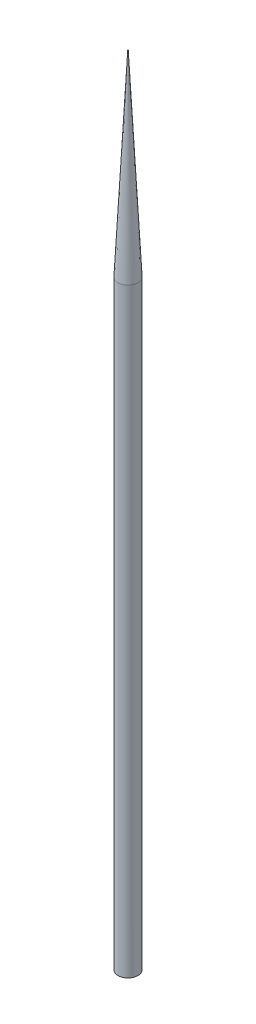
SolidWorks part; units mm, degrees
ref_plane "Спереди" through (0, 0, 0) normal (0, 0, 1) x (1, 0, 0)
ref_plane "Сверху" through (0, 0, 0) normal (0, 1, 0) x (1, 0, 0)
ref_plane "Справа" through (0, 0, 0) normal (1, 0, 0) x (0, 0, -1)
other "Configuration Table"
sketch "Эскиз1" plane through (0, 0, 0) normal (0, 1, 0) x (1, 0, 0)
  circle A0 centre (0, 0) radius 0.5
  point P4 (0, 0)
  dimension "D1" = 1
sketch "Эскиз2" plane through (0, 0, 0) normal (0, 0, 1) x (1, 0, 0)
  line L0 (0, -20.7889) -> (0, 9.2111)
  dimension "D1" = 30
  dimension "D3" = 20.7889
sweep "По траектории1" add profiles "Эскиз1" path "Эскиз2"
sketch "Эскиз5" plane through (0, 0, 0) normal (1, 0, 0) x (0, 0, -1)
  line L0 (0, 9.2111) -> (0, 19.2111) construction
  line L2 (0, 19.2111) -> (0.5, 9.2111)
  line L3 (0.5, 9.2111) -> (0, 9.2111) construction
  line L4 (0.5, 9.2111) -> (0, 9.2111)
  line L5 (0, 9.2111) -> (0, 19.2111)
  dimension "D1" = 10
revolve "Повернуть1" add sketch "Эскиз5" angle 360 about L5
scale "Масштаб1" bodies to scale 105 scale about centroid uniform scaling yes scale factor 0.7
